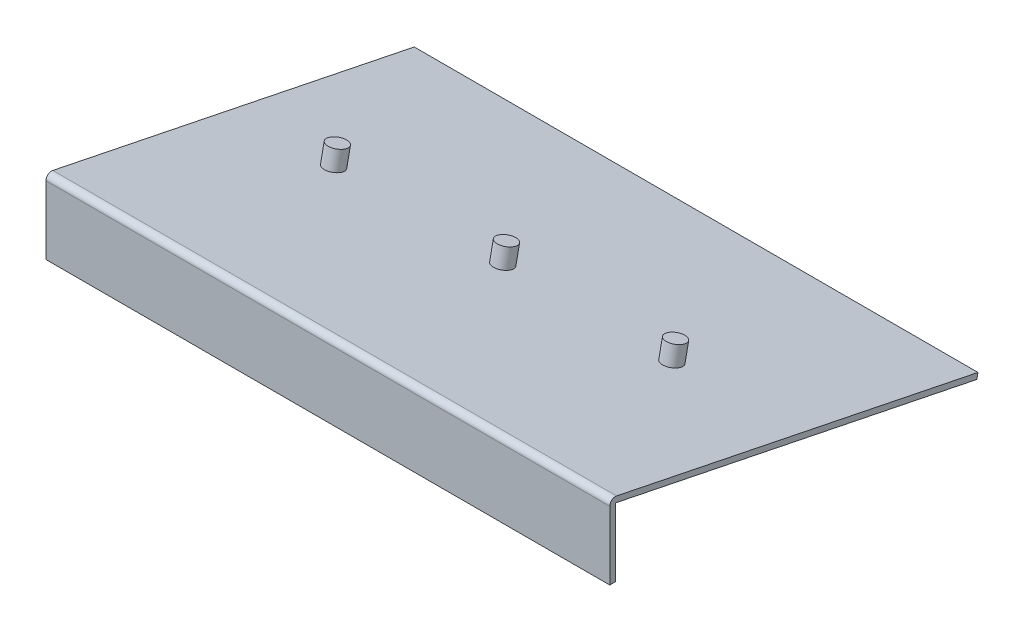
SolidWorks part; units mm, degrees
ref_plane "Front Plane" through (0, 0, 0) normal (0, 0, 1) x (1, 0, 0)
ref_plane "Top Plane" through (0, 0, 0) normal (0, 1, 0) x (1, 0, 0)
ref_plane "Right Plane" through (0, 0, 0) normal (1, 0, 0) x (0, 0, -1)
sketch "Sketch2" plane through (0, 0, 0) normal (1, 0, 0) x (0, 0, -1)
  line L0 (195.3592, -2.9394) -> (3, 36.3258)
  line L1 (195.9592, 0) -> (3.6, 39.2652)
  line L2 (0, 36.3258) -> (0, 0)
  line L3 (3, 36.3258) -> (3, 0)
  line L4 (3, 0) -> (0, 0)
  line L5 (195.9592, 0) -> (195.3592, -2.9394)
  line L6 (0, 40) -> (0, 0) construction
  line L7 (195.9592, 0) -> (0, 40) construction
  arc A0 (3.6, 39.2652) -> (0, 36.3258) centre (3, 36.3258) ccw
  dimension "D3" = 3
extrude "Boss-Extrude2" add sketch "Sketch2" along normal blind 300
sketch "Sketch3" plane through (0, 38.4, -7.8384) normal (0, 0.9798, -0.2) x (1, 0, 0)
  line L0 (0, 93.8371) -> (300, 93.8371) construction
  line L1 (0, 192) -> (0, -4.3258) construction
  line L2 (300, 192) -> (300, -4.3258) construction
  line L3 (90, 93.8371) -> (390, 93.8371) construction
  line L4 (180, 93.8371) -> (480, 93.8371) construction
  circle A0 centre (53.2645, 93.8371) radius 5
  circle A1 centre (143.2645, 93.8371) radius 5
  circle A2 centre (233.2645, 93.8371) radius 5
  dimension "D1" = 10
  dimension "D2" = 3
extrude "Boss-Extrude3" add sketch "Sketch3" along normal blind 10
